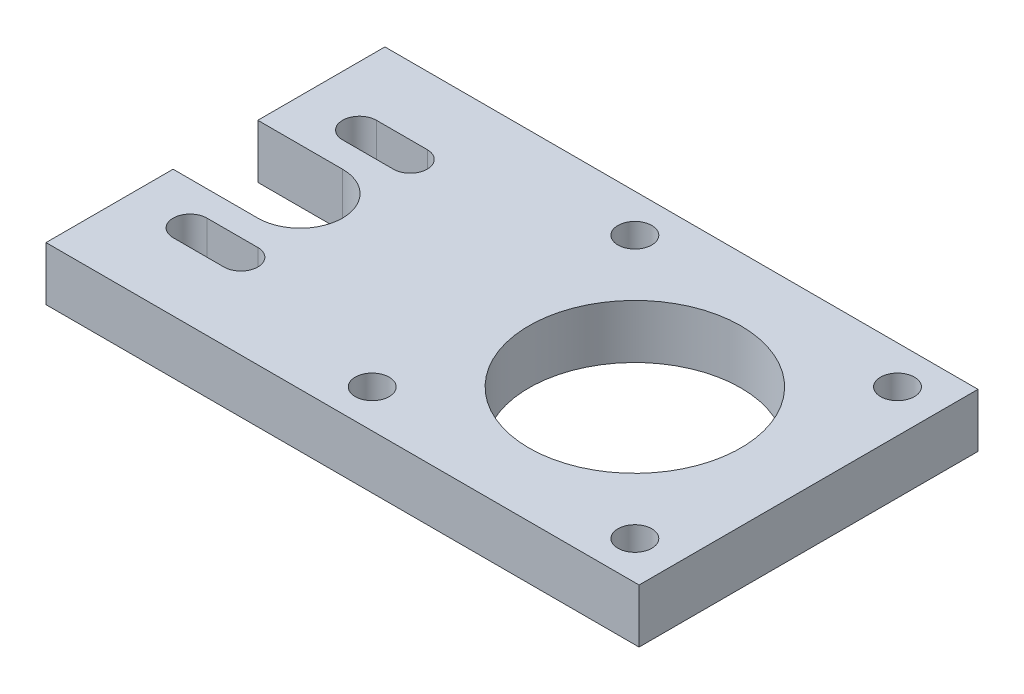
SolidWorks part; units mm, degrees
ref_plane "Front Plane" through (0, 0, 0) normal (0, 0, 1) x (1, 0, 0)
ref_plane "Top Plane" through (0, 0, 0) normal (0, 1, 0) x (1, 0, 0)
ref_plane "Right Plane" through (0, 0, 0) normal (1, 0, 0) x (0, 0, -1)
sketch "Sketch1" plane through (0, 0, 0) normal (0, 1, 0) x (1, 0, 0)
  line L1 (0, 0) -> (70, 0)
  line L2 (0, 0) -> (0, 40)
  line L3 (0, 40) -> (70, 40)
  line L4 (70, 0) -> (70, 40)
  dimension "D1" = 40
  dimension "D2" = 70
extrude "Boss-Extrude1" add sketch "Sketch1" along normal blind 6.35
sketch "Sketch2" plane through (0, 6.35, 0) normal (0, 1, 0) x (1, 0, 0)
  line L0 (0, 20) -> (70, 20) construction
  line L1 (0, 40) -> (0, 0) construction
  line L2 (70, 0) -> (70, 40) construction
  line L3 (10, 25) -> (0, 25)
  line L4 (65, 4.5) -> (34, 4.5) construction
  line L5 (65, 4.5) -> (65, 35.5) construction
  line L6 (65, 35.5) -> (34, 35.5) construction
  line L7 (34, 4.5) -> (34, 35.5) construction
  line L8 (65, 4.5) -> (34, 35.5) construction
  line L9 (65, 35.5) -> (34, 4.5) construction
  line L10 (10, 15) -> (0, 15)
  line L11 (0, 25) -> (0, 15)
  line L12 (10, 40) -> (10, 0) construction
  line L13 (70, 40) -> (0, 40) construction
  line L14 (0, 0) -> (70, 0) construction
  line L15 (13, 30) -> (7, 30) construction
  line L16 (13, 28) -> (7, 28)
  line L17 (13, 32) -> (7, 32)
  line L18 (7, 10) -> (13, 10) construction
  line L19 (7, 12) -> (13, 12)
  line L20 (7, 8) -> (13, 8)
  arc A0 (10, 15) -> (10, 25) centre (10, 20) ccw
  circle A1 centre (49.5, 20) radius 12.5
  circle A2 centre (34, 35.5) radius 2
  circle A3 centre (65, 35.5) radius 2
  circle A4 centre (65, 4.5) radius 2
  circle A5 centre (34, 4.5) radius 2
  arc A6 (13, 28) -> (13, 32) centre (13, 30) ccw
  arc A7 (7, 32) -> (7, 28) centre (7, 30) ccw
  arc A8 (7, 12) -> (7, 8) centre (7, 10) ccw
  arc A9 (13, 8) -> (13, 12) centre (13, 10) ccw
  point P29 (10, 30)
  point P35 (10, 10)
  dimension "D3" = 10
  dimension "D4" = 25
  dimension "D5" = 4
  dimension "D6" = 10
  dimension "D8" = 2
  dimension "D1" = 31
  dimension "D2" = 5
  dimension "D7" = 10
  dimension "D9" = 6
  dimension "D10" = 10
  dimension "D11" = 10
extrude "Cut-Extrude1" cut sketch "Sketch2" against normal through all
